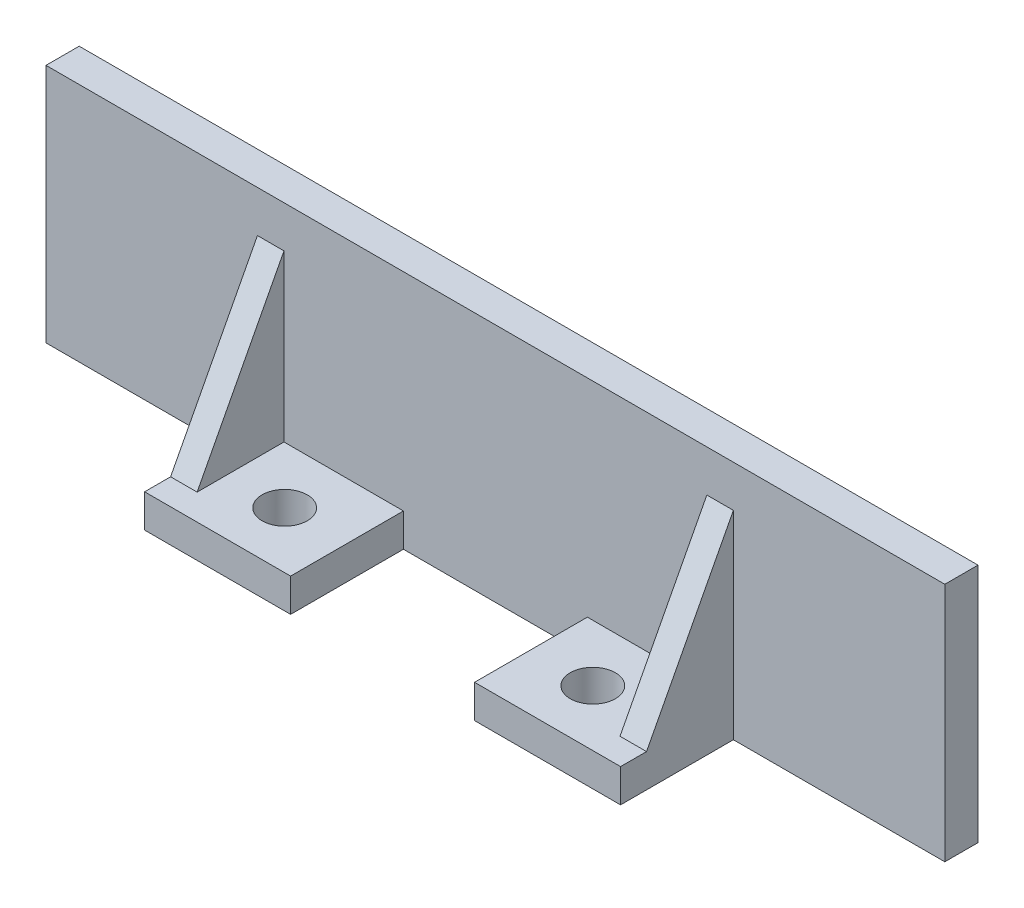
SolidWorks part; units mm, degrees
ref_plane "Front Plane" through (0, 0, 0) normal (0, 0, 1) x (1, 0, 0)
ref_plane "Top Plane" through (0, 0, 0) normal (0, 1, 0) x (1, 0, 0)
ref_plane "Right Plane" through (0, 0, 0) normal (1, 0, 0) x (0, 0, -1)
sketch "Sketch1" plane through (0, 0, 0) normal (0, 0, 1) x (1, 0, 0)
  line L1 (-43, 11.5) -> (43, 11.5)
  line L2 (-43, 11.5) -> (-43, -11.5)
  line L3 (-43, -11.5) -> (43, -11.5)
  line L4 (43, 11.5) -> (43, -11.5)
  point P0 (0, 0)
  point P5 (0, 0)
  dimension "D1" = 86
  dimension "D2" = 23
extrude "Boss-Extrude1" add sketch "Sketch1" against normal blind 3.175 contours L2 L1 L4 L3
ref_plane "Plane1" through (0, -11.5, 0) normal (0, -1, 0) x (-1, 0, 0)
sketch "Sketch3" plane through (0, -11.5, 0) normal (0, -1, 0) x (-1, 0, 0)
  line L0 (34.2, 0) -> (34.2, -10.795)
  line L1 (34.2, -10.795) -> (8.8, -10.795)
  line L2 (8.8, -10.795) -> (8.8, 0)
  line L3 (43, 0) -> (-43, 0) construction
  line L4 (34.2, 0) -> (8.8, 0)
  line L5 (0, 19.3889) -> (0, -14.044) construction
  line L6 (-34.2, 0) -> (-34.2, -10.795)
  line L7 (-34.2, -10.795) -> (-8.8, -10.795)
  line L8 (-8.8, -10.795) -> (-8.8, 0)
  line L9 (-34.2, 0) -> (-8.8, 0)
  line L10 (43, 3.175) -> (-43, 3.175) construction
  point P13 (21.5, 0)
  point P14 (0, 0)
  point P18 (34.2, -9.525)
  point P19 (34.2, -9.525)
  dimension "D2" = 13.97
  dimension "D3" = 21.5
extrude "Boss-Extrude2" add sketch "Sketch3" against normal blind 3.175
sketch "Sketch10" plane through (0, -11.5, 0) normal (0, -1, 0) x (1, 0, 0)
  line L0 (-21.5, 10.795) -> (-21.5, -3.175)
  line L1 (-8.8, 10.795) -> (-34.2, 10.795) construction
  line L2 (-43, -3.175) -> (43, -3.175) construction
ref_plane "Plane3" through (-21.5, 0, 0) normal (-1, 0, 0) x (0, 0, 1)
sketch "Sketch11" plane through (-21.5, 0, 0) normal (-1, 0, 0) x (0, 0, 1)
  line L0 (0, 7.5106) -> (8.3093, -8.325)
  line L1 (0, 11.5) -> (0, -11.5) construction
  line L2 (10.795, -8.325) -> (0, -8.325) construction
  point P6 (8.3093, -8.325)
rib "Rib4" sketch "Sketch11" sketch "Sketch11" thickness 2.54 extrusion direction parallel to sketch draft on no parameters "D1"=2.54
sketch "Sketch13" plane through (0, 11.5, 0) normal (0, 1, 0) x (1, 0, 0)
  line L0 (0, 3.175) -> (0, 0)
  line L1 (-43, 3.175) -> (43, 3.175) construction
ref_plane "Plane4" through (0, 0, 0) normal (1, 0, 0) x (0, 0, -1)
mirror "Mirror1" about plane through (0, 0, 0) normal (1, 0, 0) of "Rib4"
ref_plane "Plane6" through (0, 11.5, 0) normal (0, 1, 0) x (1, 0, 0)
sketch "Sketch17" plane through (0, 11.5, 0) normal (0, 1, 0) x (1, 0, 0)
  line L1 (-8.8, -10.795) -> (-34.2, -10.795) construction
  line L3 (-22.77, -10.795) -> (-34.2, -10.795)
  line L4 (-22.77, -10.795) -> (-22.77, 0)
  line L5 (-22.77, 0) -> (-34.2, 0)
  line L6 (-34.2, -10.795) -> (-34.2, 0)
extrude "Cut-Extrude1" cut sketch "Sketch17" against normal blind 127
mirror "Mirror2" about plane through (0, 0, 0) normal (1, 0, 0) of "Cut-Extrude1"
sketch "Sketch18" plane through (0, 11.5, 0) normal (0, 1, 0) x (1, 0, 0)
  circle A0 centre (-14.7428, -5.4218) radius 2.159
extrude "Cut-Extrude2" cut sketch "Sketch18" against normal blind 127
mirror "Mirror3" about plane through (0, 0, 0) normal (1, 0, 0) of "Cut-Extrude2"
